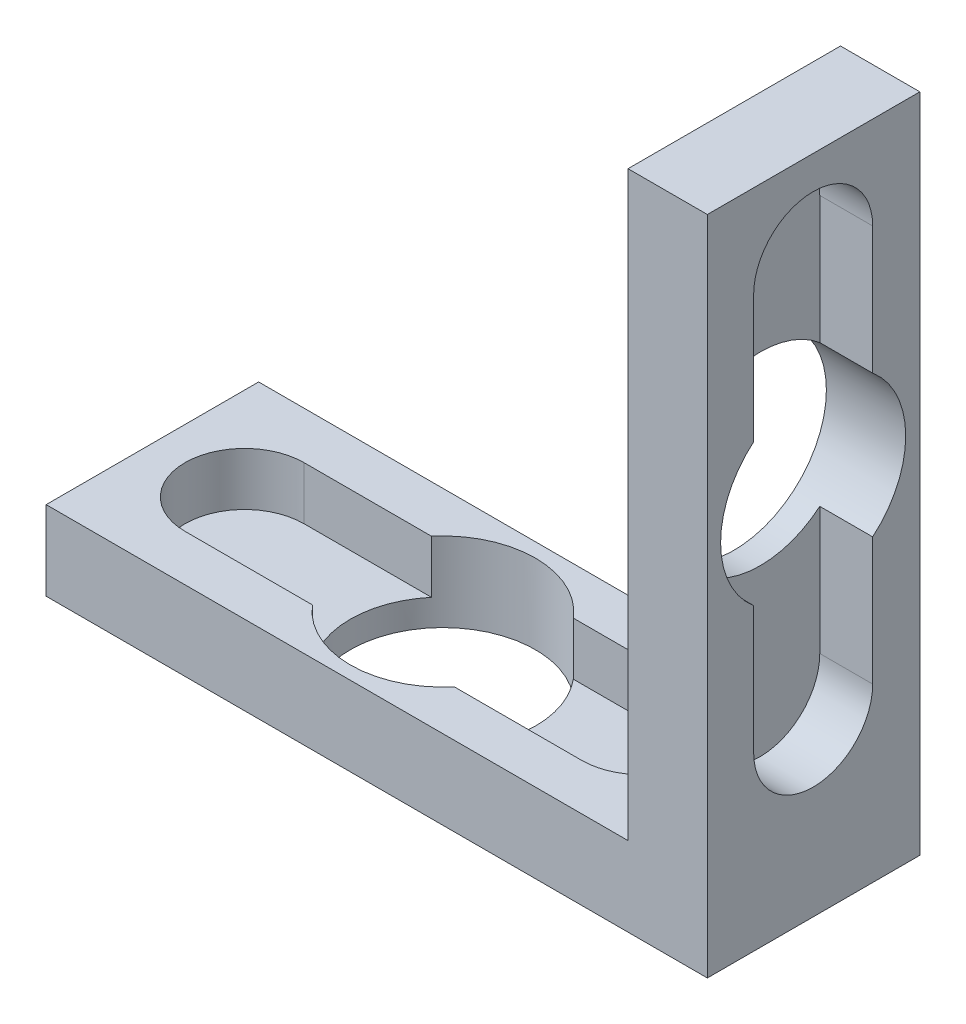
SolidWorks part; units mm, degrees
ref_plane "前视基准面" through (0, 0, 0) normal (0, 0, 1) x (1, 0, 0)
ref_plane "上视基准面" through (0, 0, 0) normal (0, 1, 0) x (1, 0, 0)
ref_plane "右视基准面" through (0, 0, 0) normal (1, 0, 0) x (0, 0, -1)
sketch "草图1" plane through (0, 0, 0) normal (0, 1, 0) x (1, 0, 0)
  line L1 (0, 0) -> (25, 0)
  line L2 (0, 0) -> (0, -8.0339)
  line L3 (0, -8.0339) -> (25, -8.0339)
  line L4 (25, 0) -> (25, -8.0339)
  dimension "D1" = 25
extrude "凸台-拉伸1" add sketch "草图1" along normal blind 3
sketch "草图2" plane through (0, 3, 0) normal (0, 1, 0) x (1, 0, 0)
  line L0 (0, -8.0339) -> (25, -8.0339) construction
  line L1 (25, -8.0339) -> (22, -8.0339)
  line L2 (25, -8.0339) -> (25, 0)
  line L3 (25, 0) -> (22, 0)
  line L4 (22, -8.0339) -> (22, 0)
  line L5 (25, 0) -> (0, 0) construction
  line L6 (25, -8.0339) -> (25, 0) construction
  dimension "D1" = 0
  dimension "D2" = 0
  dimension "D3" = 0
  dimension "D4" = 3
extrude "凸台-拉伸2" add sketch "草图2" along normal blind 22
sketch "草图3" plane through (0, 3, 0) normal (0, 1, 0) x (1, 0, 0)
  line L0 (0, -8.0339) -> (22, -8.0339) construction
  line L2 (0, 0) -> (0, -8.0339) construction
  circle A0 centre (11, -4.0339) radius 3.5
  dimension "D1" = 7
  dimension "D2" = 4
  dimension "D3" = 11
extrude "切除-拉伸1" cut sketch "草图3" against normal blind 3
sketch "草图4" plane through (0, 3, 0) normal (0, 1, 0) x (1, 0, 0)
  line L0 (22, 0) -> (22, -8.0339) construction
  line L1 (18.5, -6.2839) -> (3.5, -6.2839)
  line L2 (18.5, -6.2839) -> (18.5, -1.7839)
  line L3 (18.5, -1.7839) -> (3.5, -1.7839)
  line L4 (3.5, -6.2839) -> (3.5, -1.7839)
  line L5 (0, -8.0339) -> (22, -8.0339) construction
  dimension "D1" = 15
  dimension "D2" = 3.5
  dimension "D3" = 4.5
  dimension "D4" = 1.75
extrude "切除-拉伸2" cut sketch "草图4" against normal blind 2
sketch "草图5" plane through (0, 3, 0) normal (0, 1, 0) x (1, 0, 0)
  line L0 (18.5, -6.2839) -> (18.5, -1.7839) construction
  line L1 (3.5, -1.7839) -> (3.5, -6.2839) construction
  circle A0 centre (18.5, -4.0339) radius 2.25
  circle A1 centre (3.5, -4.0339) radius 2.25
  dimension "D1" = 4.5
  dimension "D2" = 4.5
extrude "切除-拉伸3" cut sketch "草图5" against normal blind 2
sketch "草图6" plane through (25, 0, 0) normal (1, 0, 0) x (0, 0, -1)
  line L1 (-8.0339, 25) -> (-8.0339, 0) construction
  line L2 (-8.0339, 25) -> (0, 25) construction
  circle A0 centre (-4.0339, 14) radius 3.5
  dimension "D1" = 7
  dimension "D2" = 4
  dimension "D3" = 11
extrude "切除-拉伸4" cut sketch "草图6" against normal blind 3
sketch "草图7" plane through (25, 0, 0) normal (1, 0, 0) x (0, 0, -1)
  line L0 (-8.0339, 25) -> (0, 25) construction
  line L1 (-6.2839, 6.5) -> (-1.7839, 6.5)
  line L2 (-6.2839, 6.5) -> (-6.2839, 21.5)
  line L3 (-6.2839, 21.5) -> (-1.7839, 21.5)
  line L4 (-1.7839, 6.5) -> (-1.7839, 21.5)
  line L5 (-8.0339, 25) -> (-8.0339, 0) construction
  dimension "D1" = 3.5
  dimension "D2" = 15
  dimension "D3" = 4.5
  dimension "D4" = 1.75
extrude "切除-拉伸5" cut sketch "草图7" against normal blind 2
sketch "草图8" plane through (25, 0, 0) normal (1, 0, 0) x (0, 0, -1)
  line L0 (-6.2839, 6.5) -> (-1.7839, 6.5) construction
  line L1 (-1.7839, 21.5) -> (-6.2839, 21.5) construction
  circle A0 centre (-4.0339, 6.5) radius 2.25
  circle A1 centre (-4.0339, 21.5) radius 2.25
extrude "切除-拉伸6" cut sketch "草图8" against normal blind 2
